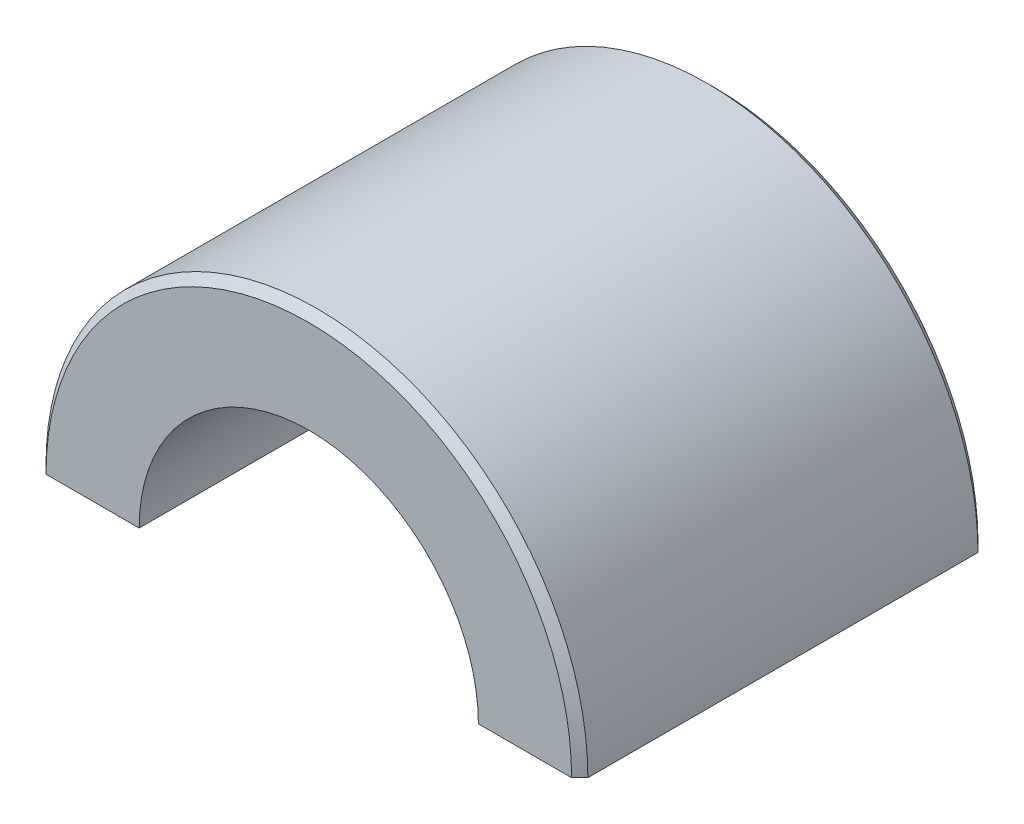
SolidWorks part; units mm, degrees
material "Brass"
ref_plane "Front" through (0, 0, 0) normal (0, 0, 1) x (1, 0, 0)
ref_plane "Top" through (0, 0, 0) normal (0, 1, 0) x (1, 0, 0)
ref_plane "Right" through (0, 0, 0) normal (1, 0, 0) x (0, 0, -1)
sketch "Sketch1" plane through (0, 0, 0) normal (0, 0, 1) x (1, 0, 0)
  line L0 (-7.9502, 0) -> (-12.7, 0)
  line L1 (7.9502, 0) -> (12.7, 0)
  arc A0 (12.7, 0) -> (-12.7, 0) centre (0, 0) ccw
  arc A1 (7.9502, 0) -> (-7.9502, 0) centre (0, 0) ccw
  dimension "D1" = 7.9502
  dimension "D2" = 12.7
extrude "Boss-Extrude1" add sketch "Sketch1" along normal blind 19.05
chamfer "Chamfer1" distance 0.381 angle 45 2 edges at (0, 12.7, 0) (0, 12.7, 19.05)
